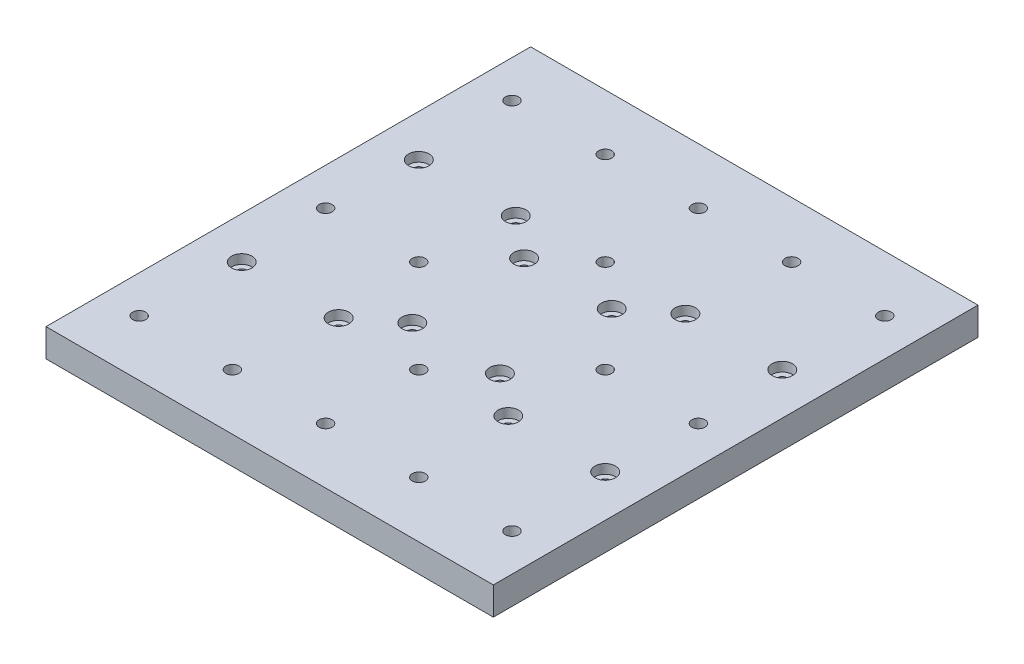
SolidWorks part; units mm, degrees
material "Haya"
ref_plane "Alzado" through (0, 0, 0) normal (0, 0, 1) x (1, 0, 0)
ref_plane "Planta" through (0, 0, 0) normal (0, 1, 0) x (1, 0, 0)
ref_plane "Vista lateral" through (0, 0, 0) normal (1, 0, 0) x (0, 0, -1)
sketch "Croquis1" plane through (0, 0, 0) normal (0, 1, 0) x (1, 0, 0)
  line L1 (-120, -130) -> (120, -130)
  line L2 (-120, -130) -> (-120, 130)
  line L3 (-120, 130) -> (120, 130)
  line L4 (120, -130) -> (120, 130)
  line L5 (-120, -130) -> (120, 130) construction
  line L6 (-120, 130) -> (120, -130) construction
  point P0 (0, 0)
  dimension "D1" = 240
  dimension "D2" = 260
extrude "Saliente-Extruir1" add sketch "Croquis1" along normal blind 15
sketch "Croquis2" plane through (0, 15, 0) normal (0, 1, 0) x (1, 0, 0)
  line L0 (-120, 0) -> (120, 0) construction
  line L1 (-120, 130) -> (-120, -130) construction
  line L2 (120, -130) -> (120, 130) construction
  line L3 (0, 130) -> (0, -130) construction
  line L4 (120, 130) -> (-120, 130) construction
  line L5 (-120, -130) -> (120, -130) construction
  line L6 (-105.5, -47.5) -> (-37.5, -47.5) construction
  line L13 (-105.5, -30) -> (-37.5, -30) construction
  line L14 (-105.5, -30) -> (-105.5, -65) construction
  line L15 (-105.5, -65) -> (-37.5, -65) construction
  line L16 (-37.5, -30) -> (-37.5, -65) construction
  line L17 (-105.5, -30) -> (-37.5, -65) construction
  line L18 (-105.5, -65) -> (-37.5, -30) construction
  circle A4 centre (-44.5, -47.5) radius 2.55
  circle A5 centre (-98.5, -47.5) radius 2.55
  circle A6 centre (98.5, -47.5) radius 2.55
  circle A7 centre (44.5, -47.5) radius 2.55
  circle A8 centre (-44.5, 47.5) radius 2.55
  circle A9 centre (-98.5, 47.5) radius 2.55
  circle A10 centre (98.5, 47.5) radius 2.55
  circle A11 centre (44.5, 47.5) radius 2.55
  point P17 (-71.5, -47.5)
  dimension "D6" = 5.1
  dimension "D1" = 65
  dimension "D2" = 68
  dimension "D3" = 35
  dimension "D4" = 48.5
  dimension "D5" = 7
  dimension "D7" = 7
sketch "Croquis6" plane through (0, 0, 0) normal (0, -1, 0) x (1, 0, 0)
  circle A0 centre (-45.5, -47.5) radius 2.55
  circle A1 centre (-97.5, -47.5) radius 2.55
  circle A2 centre (-97.5, 47.5) radius 2.55
  circle A3 centre (-45.5, 47.5) radius 2.55
  circle A4 centre (45.5, 47.5) radius 2.55
  circle A5 centre (97.5, 47.5) radius 2.55
  circle A6 centre (45.5, -47.5) radius 2.55
  circle A7 centre (97.5, -47.5) radius 2.55
  dimension "D1" = 5.1
extrude "Cortar-Extruir3" cut sketch "Croquis6" against normal through all
sketch "Croquis7" plane through (0, 15, 0) normal (0, 1, 0) x (1, 0, 0)
  circle A0 centre (-97.5, 47.5) radius 5.5
  circle A1 centre (-45.5, 47.5) radius 5.5
  circle A2 centre (-97.5, -47.5) radius 5.5
  circle A3 centre (-45.5, -47.5) radius 5.5
  circle A4 centre (45.5, -47.5) radius 5.5
  circle A5 centre (97.5, -47.5) radius 5.5
  circle A6 centre (97.5, 47.5) radius 5.5
  circle A7 centre (45.5, 47.5) radius 5.5
  dimension "D1" = 11
extrude "Cortar-Extruir4" cut sketch "Croquis7" against normal blind 5
sketch "Croquis8" plane through (0, 15, 0) normal (0, 1, 0) x (1, 0, 0)
  line L0 (-120, 130) -> (-120, -130) construction
  line L1 (120, 130) -> (-120, 130) construction
  circle A0 centre (-100, 100) radius 3.5
  circle A1 centre (-50, 100) radius 3.5
  circle A2 centre (0, 100) radius 3.5
  circle A3 centre (50, 100) radius 3.5
  circle A4 centre (100, 100) radius 3.5
  circle A5 centre (-50, 50) radius 3.5 construction
  circle A6 centre (0, 50) radius 3.5
  circle A7 centre (50, 50) radius 3.5 construction
  circle A8 centre (100, 50) radius 3.5 construction
  circle A9 centre (-50, 0) radius 3.5
  circle A10 centre (0, 0) radius 3.5 construction
  circle A11 centre (50, 0) radius 3.5
  circle A12 centre (100, 0) radius 3.5
  circle A13 centre (-50, -50) radius 3.5 construction
  circle A14 centre (0, -50) radius 3.5
  circle A15 centre (50, -50) radius 3.5 construction
  circle A16 centre (100, -50) radius 3.5 construction
  circle A17 centre (-50, -100) radius 3.5
  circle A18 centre (0, -100) radius 3.5
  circle A19 centre (50, -100) radius 3.5
  circle A20 centre (100, -100) radius 3.5
  circle A21 centre (-100, 50) radius 3.5 construction
  circle A22 centre (-100, 0) radius 3.5
  circle A23 centre (-100, -50) radius 3.5 construction
  circle A24 centre (-100, -100) radius 3.5
  dimension "D3" = 7
  dimension "D6" = 50
  dimension "D1" = 20
  dimension "D2" = 30
  dimension "D7" = 50
  dimension "D4" = 5
  dimension "D5" = 5
extrude "Cortar-Extruir5" cut sketch "Croquis8" against normal through all
sketch "Croquis9" plane through (0, 0, 0) normal (0, -1, 0) x (1, 0, 0)
  circle A0 centre (23.5, 30) radius 2.625
  circle A1 centre (-23.5, 30) radius 2.625
  circle A2 centre (-23.5, -30) radius 2.625
  circle A3 centre (23.5, -30) radius 2.625
  dimension "D1" = 5.25
extrude "Cortar-Extruir6" cut sketch "Croquis9" against normal up to next
sketch "Croquis10" plane through (0, 15, 0) normal (0, 1, 0) x (1, 0, 0)
  circle A0 centre (-23.5, -30) radius 5.5
  circle A1 centre (23.5, -30) radius 5.5
  circle A2 centre (23.5, 30) radius 5.5
  circle A3 centre (-23.5, 30) radius 5.5
  dimension "D1" = 11
extrude "Cortar-Extruir7" cut sketch "Croquis10" against normal blind 5
